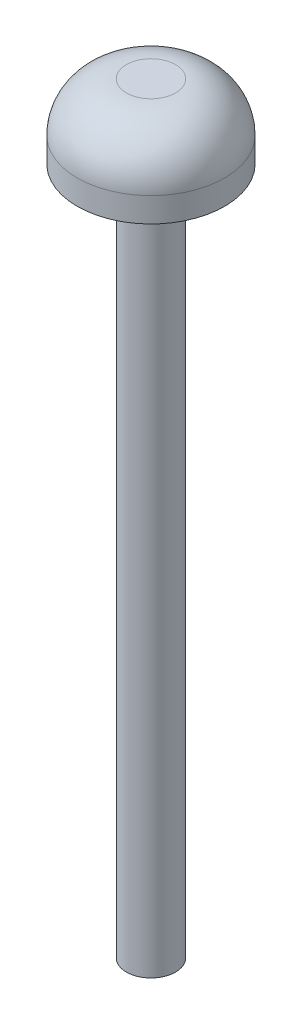
SolidWorks part; units mm, degrees
ref_plane "Front Plane" through (0, 0, 0) normal (0, 0, 1) x (1, 0, 0)
ref_plane "Top Plane" through (0, 0, 0) normal (0, 1, 0) x (1, 0, 0)
ref_plane "Right Plane" through (0, 0, 0) normal (1, 0, 0) x (0, 0, -1)
sketch "Sketch2" plane through (0, 0, 0) normal (0, 1, 0) x (1, 0, 0)
  circle A0 centre (0, 0) radius 0.5
  dimension "D1" = 1
extrude "Boss-Extrude1" add sketch "Sketch2" along normal blind 14
sketch "Sketch3" plane through (0, 14, 0) normal (0, 1, 0) x (1, 0, 0)
  circle A0 centre (0, 0) radius 1.5
  dimension "D1" = 3
extrude "Boss-Extrude2" add sketch "Sketch3" along normal blind 1.5
fillet "Fillet1" radius 1 1 edges at (0, 15.5, 1.5)
